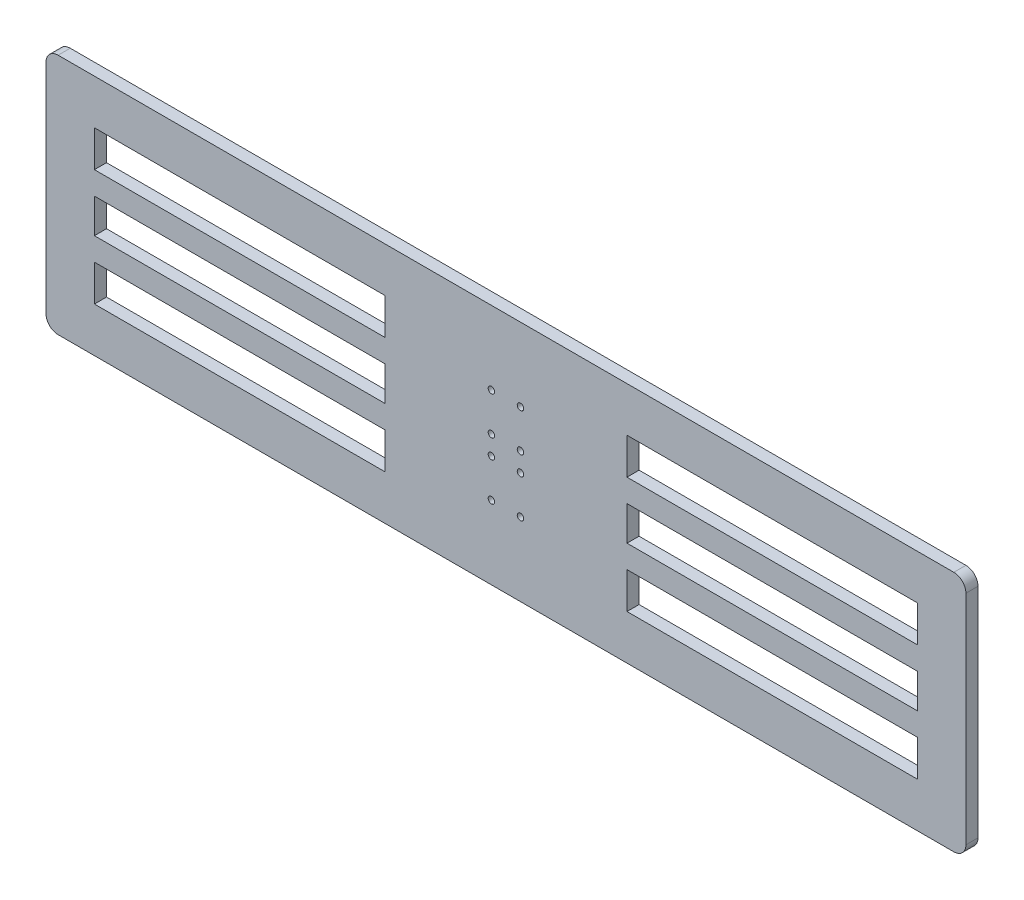
SolidWorks part; units mm, degrees
material "6061 Alloy"
ref_plane "Front Plane" through (0, 0, 0) normal (0, 0, 1) x (1, 0, 0)
ref_plane "Top Plane" through (0, 0, 0) normal (0, 1, 0) x (1, 0, 0)
ref_plane "Right Plane" through (0, 0, 0) normal (1, 0, 0) x (0, 0, -1)
sketch "Sketch1" plane through (0, 0, 0) normal (0, 0, 1) x (1, 0, 0)
  line L0 (-76.2, 50.8) -> (-76.2, -50.8)
  line L1 (-76.2, -50.8) -> (76.2, -50.8)
  line L2 (76.2, -50.8) -> (76.2, 50.8)
  line L3 (76.2, 50.8) -> (-76.2, 50.8)
  line L4 (-76.2, 0) -> (0, 0)
  line L5 (0, 0) -> (76.2, 0)
  line L6 (0, 0) -> (0, 5)
  line L7 (0, -55.88) -> (0, 55.88) construction
  line L8 (0, 5) -> (7.625, 5)
  line L9 (0, 5) -> (-7.625, 5)
  line L10 (-7.625, 5) -> (-7.625, 25)
  line L11 (-7.625, 25) -> (7.625, 25)
  line L12 (7.625, 25) -> (7.625, 5)
  line L13 (0, 0) -> (0, -5)
  line L14 (0, -5) -> (7.625, -5)
  line L15 (7.625, -5) -> (7.625, -25)
  line L16 (7.625, -25) -> (0, -25)
  line L17 (0, -25) -> (-7.625, -25)
  line L18 (-7.625, -25) -> (-7.625, -5)
  line L19 (-7.625, -5) -> (0, -5)
  line L20 (-7.625, 15) -> (7.625, 15)
  line L21 (-7.625, -15) -> (7.625, -15)
  line L22 (-76.2, 50.8) -> (-241.3, 50.8)
  line L23 (-241.3, 50.8) -> (-241.3, -50.8)
  line L24 (-241.3, -50.8) -> (-76.2, -50.8)
  line L25 (76.2, -50.8) -> (241.3, -50.8)
  line L26 (241.3, -50.8) -> (241.3, 50.8)
  line L27 (241.3, 50.8) -> (76.2, 50.8)
  line L28 (-215.9, -50.8) -> (-215.9, 50.8)
  line L29 (215.9, -50.8) -> (215.9, 50.8)
  line L30 (-215.9, 40.05) -> (-63.5, 40.05)
  line L31 (-63.5, 40.05) -> (-63.5, 21)
  line L32 (-63.5, 21) -> (-215.9, 21)
  line L33 (-241.3, -50.8) -> (-76.2, -50.8)
  line L34 (-215.9, -21) -> (-63.5, -21)
  line L35 (-63.5, -21) -> (-63.5, -40.05)
  line L36 (-63.5, -40.05) -> (-215.9, -40.05)
  line L37 (215.9, 40.05) -> (63.5, 40.05)
  line L38 (63.5, 40.05) -> (63.5, 21)
  line L39 (63.5, 21) -> (215.9, 21)
  line L40 (215.9, -40.05) -> (63.5, -40.05)
  line L41 (63.5, -40.05) -> (63.5, -21)
  line L42 (-215.9, 0) -> (-63.5, 0)
  line L43 (-63.5, 0) -> (-63.5, -9)
  line L44 (-63.5, -9) -> (-215.9, -9)
  line L45 (-63.5, 0) -> (-63.5, 9)
  line L46 (-63.5, 9) -> (-215.9, 9)
  line L47 (63.5, -21) -> (215.9, -21)
  line L48 (215.9, -9) -> (63.5, -9)
  line L49 (63.5, -9) -> (63.5, 9)
  line L50 (63.5, 9) -> (215.9, 9)
  dimension "D1" = 101.6
  dimension "D2" = 152.4
  dimension "D3" = 15
  dimension "D4" = 20
  dimension "D5" = 15.25
  dimension "D6" = 482.6
  dimension "D7" = 25.4
  dimension "D8" = 25.4
  dimension "D9" = 19.05
  dimension "D10" = 12
  dimension "D11" = 9
  dimension "D12" = 12
  dimension "D13" = 152.4
extrude "Boss-Extrude1" add sketch "Sketch1" along normal blind 6.35
sketch "Sketch2" plane through (0, 0, 6.35) normal (0, 0, 1) x (1, 0, 0)
  line L0 (7.625, 5) -> (7.625, 25)
  line L1 (7.625, 25) -> (-7.625, 25)
  line L2 (-7.625, 25) -> (-7.625, 5)
  line L3 (-7.625, 5) -> (7.625, 5)
  line L4 (7.625, -5) -> (7.625, -25)
  line L5 (7.625, -25) -> (-7.625, -25)
  line L6 (-7.625, -25) -> (-7.625, -5)
  line L7 (-7.625, -5) -> (7.625, -5)
  point P0 (7.625, 5)
  point P1 (7.625, 25)
  point P4 (7.625, -5)
  point P5 (-7.625, 25)
  point P7 (-7.625, 5)
  point P9 (7.625, -25)
  point P13 (-7.625, -25)
  point P15 (-7.625, -5)
  dimension "D1" = 20
hole_wizard "M3 Clearance Hole1" positions "Sketch2" profile "Sketch3" hole size "M3" standard "ANSI Metric" end condition up to next
sketch "Sketch3" plane through (7.625, 5, 6.35) normal (1, 0, 0) x (0, -1, 0)
  line L0 (0, 0) -> (0, 6.35)
  line L1 (0, 6.35) -> (1.7, 6.35)
  line L2 (1.7, 6.35) -> (1.7, 0)
  line L5 (1.7, 0) -> (0, 0)
  line L11 (0, -6.35) -> (0, 107.95) construction
  dimension "Thru Hole Dia." = 3.4
  dimension "Thru Hole Depth" = 6.35
fillet "Fillet1" [suppressed] radius 6.35
sketch "Sketch4" plane through (0, 0, 0) normal (0, 0, -1) x (-1, 0, 0)
  line L0 (0, 0) -> (0, 50.8)
  line L1 (0, 3.4925) -> (0, -3.4925) construction
  line L2 (0, 50.8) -> (-63.5, 50.8)
  line L3 (-63.5, 50.8) -> (-63.5, -50.8)
  line L4 (-63.5, -50.8) -> (63.5, -50.8)
  line L5 (63.5, -50.8) -> (63.5, 50.8)
  line L6 (63.5, 50.8) -> (0, 50.8)
  line L7 (-63.5, -9) -> (-63.5, 9) construction
  line L8 (-76.2, 50.8) -> (76.2, 50.8) construction
  line L9 (-63.5, 50.8) -> (-241.3, 50.8)
  line L10 (-241.3, 50.8) -> (-241.3, 63.5)
  line L11 (-241.3, 63.5) -> (241.3, 63.5)
  line L12 (241.3, 63.5) -> (241.3, 50.8)
  line L13 (-63.5, -50.8) -> (-241.3, -50.8)
  line L14 (-241.3, -50.8) -> (-241.3, -63.5)
  line L15 (-241.3, -63.5) -> (241.3, -63.5)
  line L16 (241.3, -63.5) -> (241.3, -50.8)
  line L17 (241.3, -50.8) -> (63.5, -50.8)
  line L18 (-241.3, 50.8) -> (241.3, 50.8)
  line L19 (-241.3, -50.8) -> (241.3, -50.8)
  line M34 (-241.3, -50.8) -> (241.3, -50.8)
  dimension "D1" = 127
  dimension "D2" = 101.6
  dimension "D3" = 12.7
  dimension "D4" = 12.7
extrude "Boss-Extrude2" add sketch "Sketch4" against normal up to surface (6.35 mm away) contours L15 L16 L14 M34 | L10 L11 L12 L18 up to face at (9.325, 5, 6.35)
fillet "Fillet2" radius 6.35 4 edges at (-241.3, 63.5, 3.175) (-241.3, -63.5, 3.175) (241.3, -63.5, 3.175) (241.3, 63.5, 3.175)
